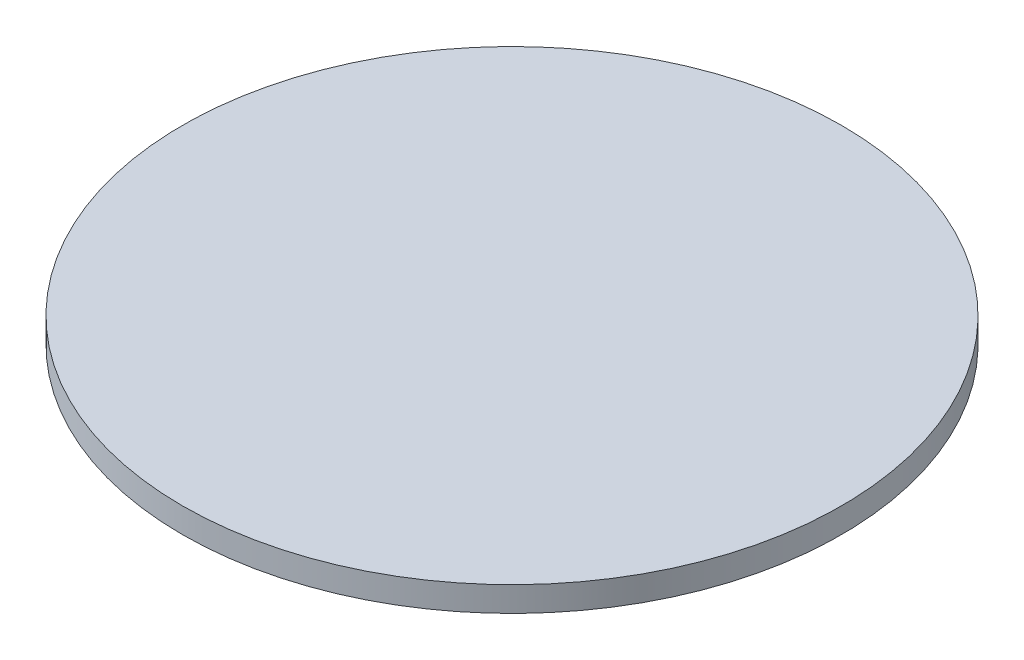
SolidWorks part; units mm, degrees
ref_plane "Front" through (0, 0, 0) normal (0, 0, 1) x (1, 0, 0)
ref_plane "Top" through (0, 0, 0) normal (0, 1, 0) x (1, 0, 0)
ref_plane "Right" through (0, 0, 0) normal (1, 0, 0) x (0, 0, -1)
sketch "Croquis1" plane through (0, 0, 0) normal (0, 1, 0) x (1, 0, 0)
  circle A0 centre (0, 0) radius 220.2937
  dimension "D1" = 440.5875
extrude "Saliente-Extruir1" add sketch "Croquis1" along normal blind 0.7937
sketch "Croquis2" plane through (0, 0, 0) normal (0, -1, 0) x (1, 0, 0)
  circle A0 centre (0, 0) radius 220.2937
  circle A1 centre (0, 0) radius 219.5
  dimension "D1" = 0.7937
extrude "Saliente-Extruir2" add sketch "Croquis2" along normal blind 15.875
sketch "Croquis3" plane through (0, 0, 0) normal (1, 0, 0) x (0, 0, -1)
  line L0 (0, 0.7937) -> (0, -15.875) construction
  line L8 (220.2937, 0.7937) -> (-220.2937, 0.7937) construction
  line L9 (-220.2937, -15.875) -> (220.2937, -15.875) construction
  line L10 (-12.7, 0.7938) -> (12.7, 0.7938)
  line L11 (12.7, 0.7938) -> (12.7, -2.3812)
  line L12 (12.7, -2.3812) -> (1.5875, -2.3812)
  line L13 (1.5875, -2.3812) -> (1.5875, -11.9062)
  line L14 (1.5875, -11.9062) -> (-1.5875, -11.9062)
  line L15 (-1.5875, -2.3812) -> (-1.5875, -11.9062)
  line L16 (-12.7, -2.3812) -> (-1.5875, -2.3812)
  line L17 (-12.7, 0.7938) -> (-12.7, -2.3812)
  point P10 (0, -11.9062)
  point P14 (0, -11.9062)
  dimension "D1" = 12.7
  dimension "D2" = 3.175
  dimension "D3" = 12.7
extrude "Saliente-Extruir3" add sketch "Croquis3" along normal up to next and the other way up to next
ref_plane "Plano1" through (-220.2629, 0, 3.6841) normal (-0.9999, 0, 0.0167) x (0.0167, 0, 0.9999)
sketch "Croquis4" plane through (-220.2629, 0, 3.6841) normal (-0.9999, 0, 0.0167) x (0.0167, 0, 0.9999)
  line L0 (9.0335, 0) -> (219.5, 0) construction
  line L1 (-12.2091, 0) -> (15.1869, 0)
  line L2 (-12.2091, 0) -> (-12.2091, -13.4659)
  line L3 (-12.2091, -13.4659) -> (15.1869, -13.4659)
  line L4 (15.1869, 0) -> (15.1869, -13.4659)
extrude "Saliente-Extruir4" add sketch "Croquis4" against normal up to surface (0.5241 mm away)
